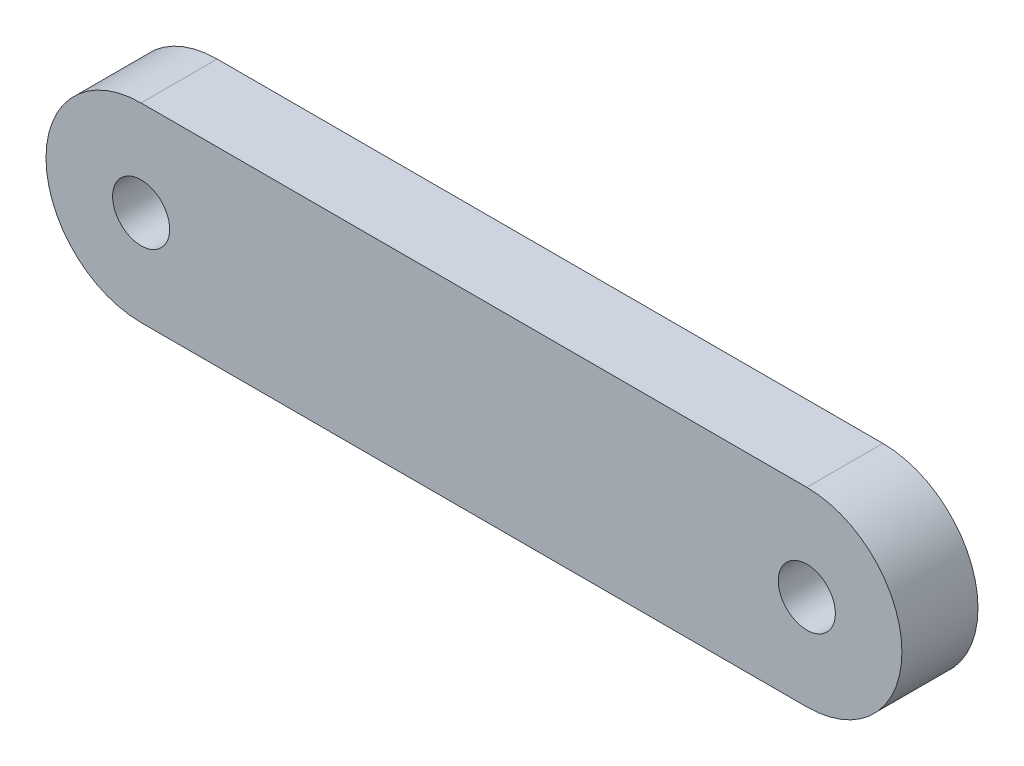
SolidWorks part; units mm, degrees
material "Maple"
ref_plane "Front Plane" through (0, 0, 0) normal (0, 0, 1) x (1, 0, 0)
ref_plane "Top Plane" through (0, 0, 0) normal (0, 1, 0) x (1, 0, 0)
ref_plane "Right Plane" through (0, 0, 0) normal (1, 0, 0) x (0, 0, -1)
sketch "Sketch1" plane through (0, 0, 0) normal (0, 0, 1) x (1, 0, 0)
  line L0 (-35, 0) -> (0, 0) construction
  line L1 (-35, 5) -> (0, 5)
  line L2 (-35, -5) -> (0, -5)
  arc A0 (-35, 5) -> (-35, -5) centre (-35, 0) ccw
  arc A1 (0, -5) -> (0, 5) centre (0, 0) ccw
  circle A2 centre (-35, 0) radius 1.5
  circle A3 centre (0, 0) radius 1.5
  point P3 (-17.5, 0)
  dimension "D1" = 35
  dimension "D2" = 5
  dimension "D3" = 3
extrude "Boss-Extrude1" add sketch "Sketch1" along normal blind 4
